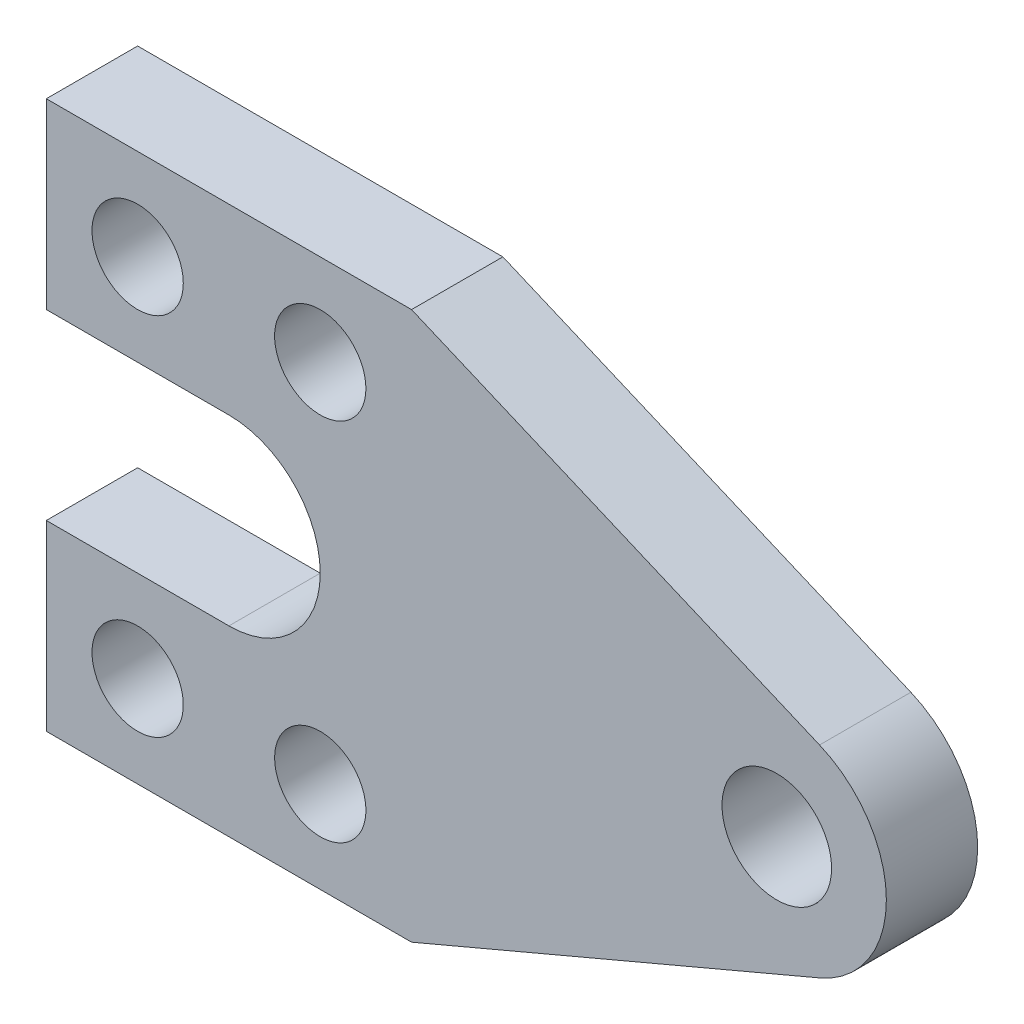
SolidWorks part; units mm, degrees
ref_plane "Front Plane" through (0, 0, 0) normal (0, 0, 1) x (1, 0, 0)
ref_plane "Top Plane" through (0, 0, 0) normal (0, 1, 0) x (1, 0, 0)
ref_plane "Right Plane" through (0, 0, 0) normal (1, 0, 0) x (0, 0, -1)
sketch "Sketch1" plane through (0, 0, 0) normal (0, 0, 1) x (1, 0, 0)
  line L0 (10, 70) -> (50, 70)
  line L1 (50, 70) -> (94.6856, 51.0474)
  line L2 (94.6856, 28.9526) -> (50, 10)
  line L3 (50, 10) -> (10, 10)
  line L4 (10, 10) -> (10, 30)
  line L5 (10, 30) -> (30, 30)
  line L7 (30, 50) -> (10, 50)
  line L8 (10, 50) -> (10, 70)
  line L9 (22.551, 40) -> (50022.551, 40) construction
  arc A0 (94.6856, 51.0474) -> (94.6856, 28.9526) centre (90, 40) cw
  arc A1 (30, 50) -> (30, 30) centre (30, 40) cw
  circle A2 centre (90, 40) radius 6
  circle A3 centre (20, 60) radius 5
  circle A4 centre (40, 60) radius 5
  circle A5 centre (40, 20) radius 5
  circle A6 centre (20, 20) radius 5
  point P16 (40, 40)
  point P21 (0, 0)
  point P22 (0, 0)
  point P23 (29.71, 63.487)
  dimension "D1" = 10
  dimension "D3" = 12
  dimension "D7" = 12
  dimension "D8" = 10
  dimension "D9" = 10
  dimension "D12" = 10
  dimension "D2" = 10
  dimension "D4" = 80
  dimension "D5" = 60
  dimension "D6" = 40
  dimension "D10" = 20
  dimension "D11" = 10
  dimension "D13" = 20
extrude "Boss-Extrude1" add sketch "Sketch1" along normal blind 10
